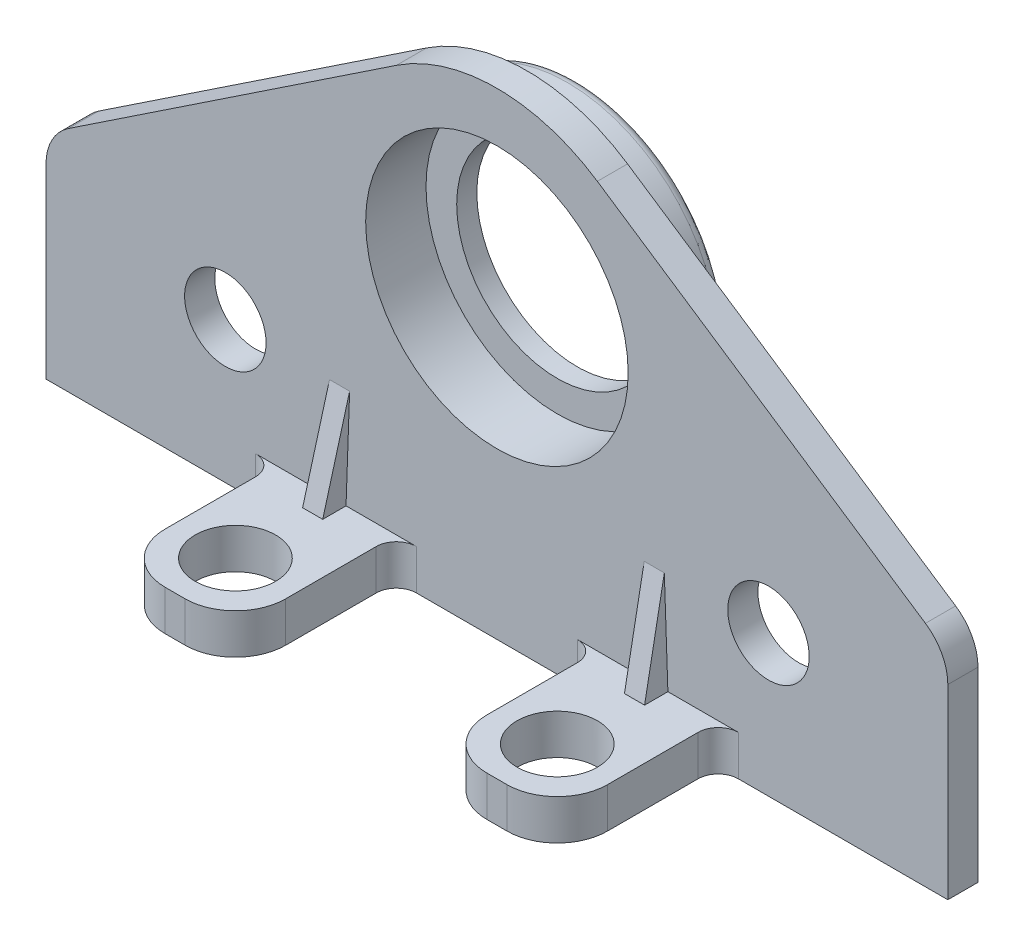
SolidWorks part; units mm, degrees
other "Triangulo" parameters "D1"=39.9603, "D2"=11.6077, "D3"=8.4742, "D4"=1.8044
ref_plane "Alzado" through (0, 0, 0) normal (0, 0, 1) x (1, 0, 0)
ref_plane "Planta" through (0, 0, 0) normal (0, 1, 0) x (1, 0, 0)
ref_plane "Vista lateral" through (0, 0, 0) normal (1, 0, 0) x (0, 0, -1)
sketch "Croquis1" plane through (0, 0, 0) normal (0, 0, 1) x (1, 0, 0)
  line L0 (-7.4893, 0) -> (7.4893, 0)
  line L1 (-7.4893, 0) -> (0.0007, 21.6199)
  line L2 (0.0007, 21.6199) -> (7.4893, 0)
  line L3 (0, -7.4828) -> (0, 20.2315) construction
  dimension "D1" = 14.9787
  dimension "D2" = 21.6199
extrude "Saliente-Extruir1" add sketch "Croquis1" along normal mid plane 46
sketch "Croquis2" plane through (0, 0, 23) normal (0, 0, 1) x (1, 0, 0)
  line L0 (0, 0) -> (0, 22.9126) construction
  line L1 (37.4468, 0) -> (-37.4468, 0)
  line L2 (0.0007, 21.6199) -> (-37.4468, 0)
  line L3 (0.0007, 21.6199) -> (37.4468, 0)
  point P6 (0, 0)
  dimension "D1" = 74.8935
extrude "Saliente-Extruir2" add sketch "Croquis2" along normal blind 2
mirror "Simetría1" about plane through (0, 0, 0) normal (0, 0, 1) of "Saliente-Extruir2"
sketch "Croquis3" plane through (0, 0, 0) normal (0, -1, 0) x (1, 0, 0)
  line L1 (-37.4468, 25) -> (37.4468, 25)
  line L2 (-37.4468, 25) -> (-37.4468, -25)
  line L3 (-37.4468, -25) -> (37.4468, -25)
  line L4 (37.4468, 25) -> (37.4468, -25)
extrude "Saliente-Extruir3" add sketch "Croquis3" along normal blind 2 contours L2 L3 L4 L1
sketch "Croquis4" plane through (0, 0, 25) normal (0, 0, 1) x (1, 0, 0)
  line L0 (0, -2) -> (0, -6.2) construction
  line L1 (-37.4468, -2) -> (37.4468, -2) construction
  line L5 (7.7435, -2) -> (-7.7435, -2)
  circle A0 centre (0, -6.2) radius 4.05
  arc A1 (5.8197, -4.5466) -> (-5.8197, -4.5466) centre (0, -6.2) cw
  arc A2 (-5.8197, -4.5466) -> (-7.7435, -2) centre (-7.7435, -4) ccw
  arc A3 (5.8197, -4.5466) -> (7.7435, -2) centre (7.7435, -4) cw
  dimension "D2" = 8.1
  dimension "D4" = 2
  dimension "D1" = 4.2
  dimension "D3" = 2
extrude "Saliente-Extruir4" add sketch "Croquis4" against normal up to surface (50 mm away) contours A0
chamfer "Chaflán2" distance 1 angle 45 2 edges at (4.05, -6.2, 25) (4.05, -6.2, -25)
sketch "Croquis6" plane through (0, 0, -25) normal (0, 0, -1) x (-1, 0, 0)
  line L12 (-13.9105, 17.8924) -> (-35.5298, -19.554)
  line L13 (-35.5298, -19.554) -> (-34.5298, -21.2861)
  line L14 (-34.5298, -21.2861) -> (-8.8061, -6.4345)
  line L15 (4.6061, 1.3091) -> (30.3298, 16.1607)
  line L16 (30.3298, 16.1607) -> (29.3298, 17.8927)
  line L17 (29.3298, 17.8927) -> (-13.9105, 17.8924)
  circle A2 centre (0, -6.2) radius 4.05
  arc A6 (-5.8667, -7.6779) -> (-8.8061, -6.4345) centre (-7.8061, -8.1665) ccw
  arc A7 (-5.8667, -7.6779) -> (4.2133, -1.8583) centre (0, -6.2) ccw
  arc A8 (4.6061, 1.3091) -> (4.2133, -1.8583) centre (5.6061, -0.423) ccw
sketch "Croquis7" plane through (0, 0, -25) normal (0, 0, -1) x (-1, 0, 0)
  line L0 (-34.5298, -21.2861) -> (-8.8061, -6.4345) construction
  line L1 (0, -27.6467) -> (0, 26.7412) construction
  line L3 (-9.9862, 8.7759) -> (-42.6054, -12.9752)
  line L4 (-24.9825, -1.2852) -> (-44.8315, -35.6653) construction
  line L5 (9.9862, 8.7759) -> (42.6054, -12.9752)
  line L6 (-13.9105, 17.8924) -> (-35.5298, -19.554) construction
  line L7 (-44.8315, -35.6653) -> (44.8315, -35.6653)
  line L8 (-44.8315, -17.1352) -> (-44.8315, -35.6653)
  line L9 (44.8315, -17.1352) -> (44.8315, -35.6653)
  line L10 (27, -25.6653) -> (-27, -25.6653) construction
  circle A0 centre (-27, -21.6153) radius 4.05
  circle A1 centre (0, -6.2) radius 4.05 construction
  circle A2 centre (27, -21.6153) radius 4.05
  arc A3 (9.9862, 8.7759) -> (-9.9862, 8.7759) centre (0, -6.2) ccw
  circle A6 centre (0, -6.2) radius 13.05
  arc A9 (44.8315, -17.1352) -> (42.6054, -12.9752) centre (39.8315, -17.1352) ccw
  arc A10 (-44.8315, -17.1352) -> (-42.6054, -12.9752) centre (-39.8315, -17.1352) cw
  point P21 (44.8315, -14.4596)
  point P26 (-44.8315, -14.4596)
  point P27 (44.8315, -34.7878)
  point P33 (-40.202, -35.6653)
  point P34 (-44.7932, -35.6653)
  point P35 (-44.1434, -35.599)
  dimension "D1" = 8.1
  dimension "D2" = 27
  dimension "D3" = 5
  dimension "D4" = 18
  dimension "D6" = 26.1
  dimension "D5" = 10
extrude "Saliente-Extruir5" add sketch "Croquis7" along normal blind 6 separate body
sketch "Croquis8" plane through (0, 0, -25) normal (0, 0, 1) x (1, 0, 0)
  line L0 (44.8315, -35.6653) -> (-44.8315, -35.6653) construction
  line L1 (-22, -35.6653) -> (-10, -35.6653)
  line L2 (-22, -35.6653) -> (-22, -31.6653)
  line L3 (-22, -31.6653) -> (-10, -31.6653)
  line L4 (-10, -35.6653) -> (-10, -31.6653)
  line L5 (0, 11.8) -> (0, -38.4199) construction
  line L6 (22, -31.6653) -> (10, -31.6653)
  line L7 (10, -35.6653) -> (10, -31.6653)
  line L8 (22, -35.6653) -> (10, -35.6653)
  line L9 (22, -35.6653) -> (22, -31.6653)
  arc A0 (9.9862, 8.7759) -> (-9.9862, 8.7759) centre (0, -6.2) ccw construction
  point P4 (10, -28.3518)
  point P5 (10, -29.8809)
  point P17 (-22, -25.6189)
  point P18 (-22, -27.6467)
  dimension "D1" = 12
  dimension "D2" = 4
  dimension "D3" = 10
extrude "Saliente-Extruir6" add sketch "Croquis8" along normal blind 16
fillet "Redondeo3" radius 2 4 edges at (22, -33.6653, -25) (10, -33.6653, -25) (-10, -33.6653, -25) (-22, -33.6653, -25)
fillet "Redondeo4" radius 5 4 edges at (22, -33.6653, -9) (10, -33.6653, -9) (-22, -33.6653, -9) (-10, -33.6653, -9)
sketch "Croquis14" plane through (0, -31.6653, 0) normal (0, 1, 0) x (1, 0, 0)
  line L0 (0, 0) -> (0, 45.0228) construction
  line L1 (-22, 14) -> (-22, 23) construction
  line L2 (-15, 9) -> (-17, 9) construction
  circle A0 centre (-16, 15) radius 4
  circle A1 centre (16, 15) radius 4
  dimension "D1" = 6
  dimension "D2" = 6
  dimension "D3" = 8
extrude "Cortar-Extruir1" cut sketch "Croquis14" against normal blind 10 contours A0 | A1
sketch "Croquis16" plane through (0, -31.6653, 0) normal (0, 1, 0) x (1, 0, 0)
  line L0 (-16, 25) -> (-16, 22.6812)
  line L1 (-8, 25) -> (-24, 25) construction
sketch3d "Croquis3D2"
  line L0 (-27, -21.6153, -25) -> (-4.2911, -21.6153, -25) construction
  line L1 (-27, -21.6153, -31) -> (-27, -21.6153, -25) construction
  line L2 (-16, -31.6653, -22.6812) -> (-15.6455, -21.6153, -25)
  line L3 (-16, -31.6653, -22.6812) -> (-16, -31.6653, -25)
  line L4 (-16, -31.6653, -25) -> (-15.6455, -21.6153, -25)
extrude "Saliente-Extruir7" add sketch "Croquis3D2" along direction (1, 0, 0) on the side of the normal mid plane 2 contours L2 L4 L3
mirror "Simetría2" about plane through (0, 0, 0) normal (1, 0, 0) of "Saliente-Extruir7"
sketch "Croquis20" plane through (0, 0, -31) normal (0, 0, -1) x (-1, 0, 0)
  line L3 (42.6054, -12.9752) -> (9.9862, 8.7759)
  line L4 (-9.9862, 8.7759) -> (-42.6054, -12.9752)
  line L5 (-44.8315, -17.1352) -> (-44.8315, -35.6653)
  line L6 (42.6054, -12.9752) -> (9.9862, 8.7759)
  line L7 (-9.9862, 8.7759) -> (-42.6054, -12.9752)
  line L11 (-44.8315, -17.1352) -> (-44.8315, -35.6653)
  line L12 (-44.8315, -35.6653) -> (44.8315, -35.6653)
  line L13 (-44.8315, -35.6653) -> (44.8315, -35.6653)
  line L14 (44.8315, -35.6653) -> (44.8315, -17.1352)
  line L15 (44.8315, -35.6653) -> (44.8315, -17.1352)
  circle A0 centre (-27, -21.6153) radius 4.05 construction
  circle A1 centre (-27, -21.6153) radius 4.05
  circle A2 centre (27, -21.6153) radius 4.05 construction
  arc A3 (44.8315, -17.1352) -> (42.6054, -12.9752) centre (39.8315, -17.1352) ccw
  arc A4 (9.9862, 8.7759) -> (-9.9862, 8.7759) centre (0, -6.2) ccw
  arc A5 (44.8315, -17.1352) -> (42.6054, -12.9752) centre (39.8315, -17.1352) ccw
  arc A7 (9.9862, 8.7759) -> (-9.9862, 8.7759) centre (0, -6.2) ccw
  circle A9 centre (27, -21.6153) radius 4.05
  circle A10 centre (0, -6.2) radius 10
  arc A14 (-42.6054, -12.9752) -> (-44.8315, -17.1352) centre (-39.8315, -17.1352) ccw
  arc A15 (-42.6054, -12.9752) -> (-44.8315, -17.1352) centre (-39.8315, -17.1352) ccw
  dimension "D2" = 20
  dimension "D1" = 0
extrude "Saliente-Extruir8" add sketch "Croquis20" along normal blind 2
chamfer "Chaflán3" distance 1 angle 45 2 edges at (22.95, -21.6153, -33) (-31.05, -21.6153, -33)
delete or keep bodies "Sólido-Eliminar/Conservar 1" type delete bodies bodies 105
sketch "Croquis22" plane through (0, 0, -33) normal (0, 0, -1) x (-1, 0, 0)
  circle A0 centre (0, -6.2) radius 15
  dimension "D1" = 30
extrude "Cortar-Extruir3" cut sketch "Croquis22" against normal blind 5
fillet "Redondeo6" radius 1 2 edges at (-15, -6.2, -33) (-15, -6.2, -28)
equation "\"B\"= 74.8935"
equation "\"h\"= 21.6199"
equation "\"an\"= 30°"
equation "\"w\"=4"
equation "\"z\"= 2"
equation "\"p\"= 50"
equation "\"r\"= 8"
equation "\"base\"= \"B\" / 5"
equation "\"D1@Croquis1\"=\"base\""
equation "\"D2@Croquis1\"=\"h\""
equation "\"D1@Saliente-Extruir1\"=\"p\"-2*\"z\""
equation "\"D1@Croquis2\"=\"B\""
equation "\"D1@Croquis4\"=\"w\"+0.2"
